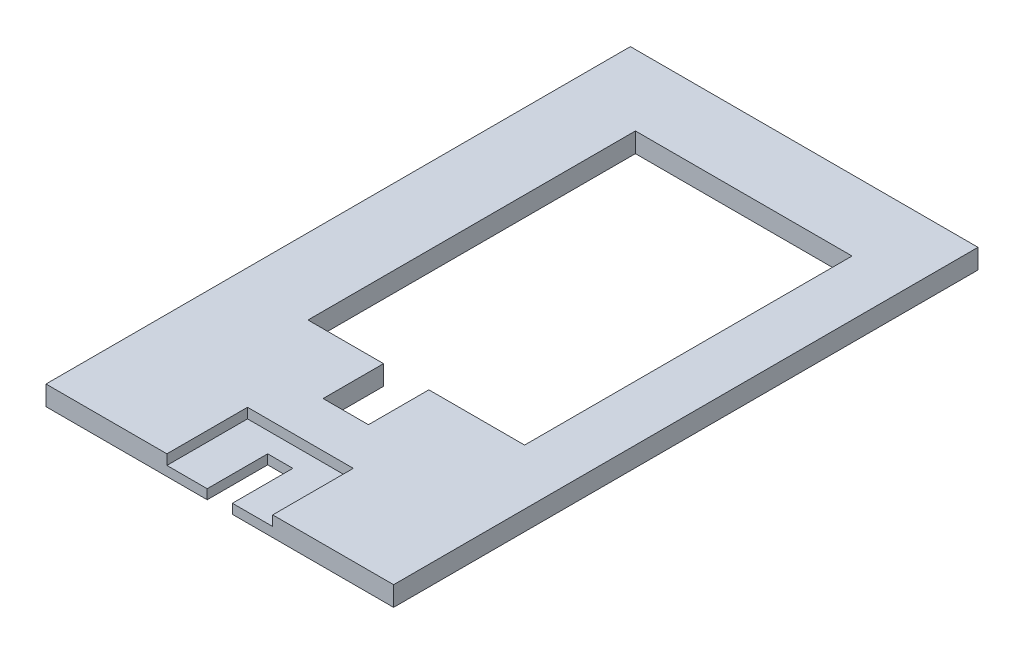
SolidWorks part; units mm, degrees
ref_plane "Front Plane" through (0, 0, 0) normal (0, 0, 1) x (1, 0, 0)
ref_plane "Top Plane" through (0, 0, 0) normal (0, 1, 0) x (1, 0, 0)
ref_plane "Right Plane" through (0, 0, 0) normal (1, 0, 0) x (0, 0, -1)
sketch "Sketch1" plane through (0, 0, 0) normal (0, 1, 0) x (1, 0, 0)
  line L5 (187.5728, -173.3374) -> (-157.4272, -173.3374)
  line L6 (187.5728, -173.3374) -> (187.5728, 406.6626)
  line L7 (187.5728, 406.6626) -> (-157.4272, 406.6626)
  line L8 (-157.4272, -173.3374) -> (-157.4272, 406.6626)
  dimension "D1" = 345
  dimension "D2" = 580
extrude "Boss-Extrude1" add sketch "Sketch1" along normal blind 19.53 contours L7 L8 L5 L6
sketch "Sketch2" plane through (0, 19.53, 0) normal (0, 1, 0) x (1, 0, 0)
  line L0 (-157.4272, -173.3374) -> (-157.4272, 406.6626) construction
  line L1 (-82.4272, 336.6626) -> (132.5728, 336.6626)
  line L2 (-82.4272, 336.6626) -> (-82.4272, 11.6626)
  line L3 (-82.4272, 11.6626) -> (132.5728, 11.6626)
  line L4 (132.5728, 336.6626) -> (132.5728, 11.6626)
  line L5 (187.5728, -173.3374) -> (187.5728, 406.6626) construction
  line L6 (187.5728, 406.6626) -> (-157.4272, 406.6626) construction
  dimension "D1" = 325
  dimension "D2" = 75
  dimension "D3" = 55
  dimension "D4" = 70
extrude "Cut-Extrude1" cut sketch "Sketch2" against normal up to next and the other way through all
sketch "Sketch3" plane through (0, 19.53, 0) normal (0, 1, 0) x (1, 0, 0)
  line L0 (132.5728, 11.6626) -> (-82.4272, 11.6626) construction
  line L1 (-7.4272, 11.6626) -> (37.5728, 11.6626)
  line L2 (-7.4272, 11.6626) -> (-7.4272, -48.3374)
  line L3 (-7.4272, -48.3374) -> (37.5728, -48.3374)
  line L4 (37.5728, 11.6626) -> (37.5728, -48.3374)
  line L5 (-157.4272, -173.3374) -> (-157.4272, 406.6626) construction
  line L6 (187.5728, -173.3374) -> (187.5728, 406.6626) construction
  dimension "D1" = 150
  dimension "D2" = 150
  dimension "D3" = 60
extrude "Cut-Extrude2" cut sketch "Sketch3" against normal blind 19.53
sketch "Sketch4" plane through (0, 19.53, 0) normal (0, 1, 0) x (1, 0, 0)
  line L0 (187.5728, -173.3374) -> (-157.4272, -173.3374) construction
  line L1 (-37.4272, -93.3374) -> (67.5728, -93.3374)
  line L2 (-37.4272, -93.3374) -> (-37.4272, -173.3374)
  line L3 (-37.4272, -173.3374) -> (67.5728, -173.3374)
  line L4 (67.5728, -93.3374) -> (67.5728, -173.3374)
  line L5 (-157.4272, -173.3374) -> (-157.4272, 406.6626) construction
  line L6 (187.5728, -173.3374) -> (187.5728, 406.6626) construction
  dimension "D1" = 120
  dimension "D2" = 120
  dimension "D3" = 80
extrude "Cut-Extrude3" cut sketch "Sketch4" against normal blind 10
sketch "Sketch5" plane through (0, 9.53, 0) normal (0, 1, 0) x (1, 0, 0)
  line L0 (-37.4272, -173.3374) -> (67.5728, -173.3374) construction
  line L1 (2.5728, -113.3374) -> (27.5728, -113.3374)
  line L2 (2.5728, -113.3374) -> (2.5728, -173.3374)
  line L3 (2.5728, -173.3374) -> (27.5728, -173.3374)
  line L4 (27.5728, -113.3374) -> (27.5728, -173.3374)
  line L5 (-157.4272, -173.3374) -> (-157.4272, 406.6626) construction
  line L6 (187.5728, -173.3374) -> (187.5728, 406.6626) construction
  dimension "D1" = 60
  dimension "D2" = 160
  dimension "D3" = 160
extrude "Cut-Extrude4" cut sketch "Sketch5" against normal blind 10
